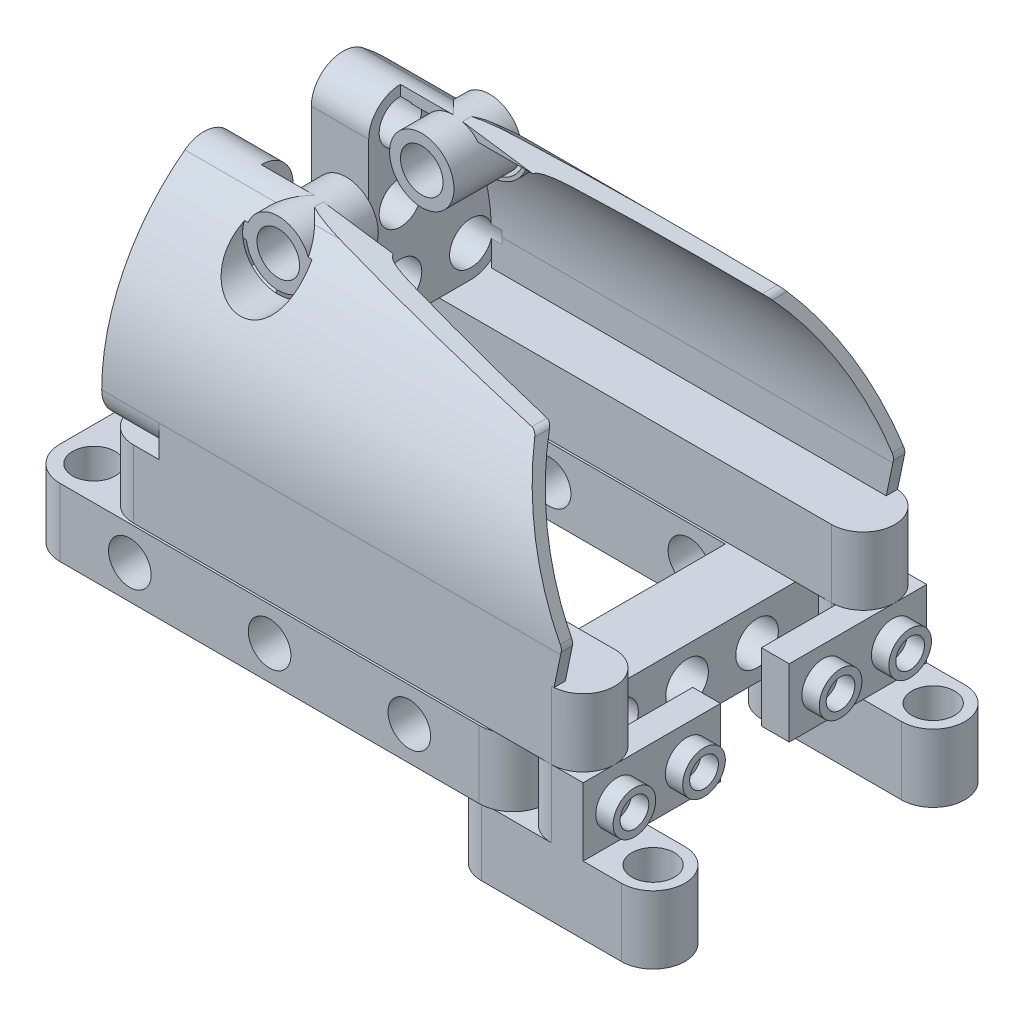
SolidWorks part; units mm, degrees
ref_plane "Front Plane" through (0, 0, 0) normal (0, 0, 1) x (1, 0, 0)
ref_plane "Top plane" through (0, 0, 0) normal (0, 1, 0) x (1, 0, 0)
ref_plane "Right plane" through (0, 0, 0) normal (1, 0, 0) x (0, 0, -1)
sketch "Sketch1" plane through (0, 0, 0) normal (0, 1, 0) x (1, 0, 0)
  line L0 (-8.05, 0) -> (8.05, 0) construction
  line L1 (-8.05, 3.65) -> (8.05, 3.65)
  line L2 (-8.05, -3.65) -> (8.05, -3.65)
  arc A0 (-8.05, 3.65) -> (-8.05, -3.65) centre (-8.05, 0) ccw
  arc A1 (8.05, -3.65) -> (8.05, 3.65) centre (8.05, 0) ccw
  point P2 (0, 0)
  point P7 (11.7, 0)
  point P9 (-11.7, 0)
  dimension "D1" = 7.3
  dimension "D2" = 23.4
extrude "Boss-Extrude1" add sketch "Sketch1" along normal blind 7.8
sketch "Sketch2" plane through (0, 7.8, 0) normal (0, 1, 0) x (1, 0, 0)
  line L0 (-52.6, 0) -> (-14.3812, 0) construction
  line L1 (-8.05, 3.9) -> (-56.25, 3.9)
  line L2 (-4.15, 0) -> (-4.15, -16.1)
  line L4 (-60.15, 0) -> (-60.15, -16.1)
  line L5 (-52.35, -16.1) -> (-52.35, -3.9)
  line L6 (-52.35, -3.9) -> (-11.95, -3.9)
  line L7 (-11.95, -3.9) -> (-11.95, -16.1)
  line L8 (-11.95, -16.1) -> (-4.15, -16.1)
  line L9 (-52.35, -16.1) -> (-60.15, -16.1)
  line L10 (-26.0708, -3.9) -> (-26.0708, 3.9) construction
  line L11 (-8.05, 0) -> (8.05, 0) construction
  line L12 (0, 3.65) -> (3.65, 3.65)
  line L13 (-8.05, 3.65) -> (8.05, 3.65) construction
  line L14 (3.65, 3.65) -> (3.65, -12.15)
  line L15 (3.65, -12.15) -> (0.45, -12.15)
  line L16 (0.45, -12.15) -> (0.45, -3.65)
  line L17 (-8.05, -3.65) -> (8.05, -3.65) construction
  line L18 (0, -3.65) -> (0.45, -3.65)
  arc A2 (-8.05, 3.9) -> (-4.15, 0) centre (-8.05, 0) cw
  arc A3 (-60.15, 0) -> (-56.25, 3.9) centre (-56.25, 0) cw
  arc A7 (-8.05, 3.65) -> (-8.05, -3.65) centre (-8.05, 0) ccw construction
  arc A8 (0, 3.65) -> (0, -3.65) centre (0, 0) ccw
  point P18 (-26.0708, 0)
  dimension "D1" = 56
  dimension "D2" = 7.8
  dimension "D3" = 20
  dimension "D4" = 15.8
  dimension "D5" = 3.2
extrude "Boss-Extrude2" add sketch "Sketch2" along normal blind 7.8 contours A2 L2 L8 L7 L6 L5 L9 L4 A3 L1 | A8 L18 L16 L15 L14 L12
sketch "Sketch3" plane through (0, 15.6, 0) normal (0, 1, 0) x (1, 0, 0)
  line L0 (-48.05, 0) -> (0, 0) construction
  line L1 (-48.05, 3.65) -> (0, 3.65)
  line L2 (-48.05, -3.65) -> (0, -3.65)
  arc A0 (-48.05, 3.65) -> (-48.05, -3.65) centre (-48.05, 0) ccw
  arc A1 (0, -3.65) -> (0, 3.65) centre (0, 0) ccw
  arc A2 (8.05, -3.65) -> (8.05, 3.65) centre (8.05, 0) ccw construction
  point P3 (-24.025, 0)
  point P11 (-51.7, 0)
  point P12 (3.65, 0)
  dimension "D1" = 55.35
extrude "Boss-Extrude3" add sketch "Sketch3" along normal blind 7.8
ref_plane "Plane1" through (-51.7, 0, 0) normal (-1, 0, 0) x (0, 0, 1)
sketch "Sketch5" plane through (-51.7, 0, 0) normal (-1, 0, 0) x (0, 0, 1)
  line L1 (3.65, 23.4) -> (-3.65, 23.4) construction
  line L2 (0, 23.4) -> (8.1, 23.4)
  line L3 (11.75, 27.05) -> (11.75, 43.25)
  arc A0 (-3.65, 27.05) -> (0, 23.4) centre (0, 27.05) ccw
  arc A1 (8.1, 23.4) -> (11.75, 27.05) centre (8.1, 27.05) ccw
  arc A2 (11.75, 43.25) -> (5.91, 46.17) centre (8.1, 43.25) ccw
  arc A3 (-3.65, 27.05) -> (5.91, 46.17) centre (20.25, 27.05) cw
  point P2 (-3.65, 27.05)
  point P4 (11.75, 27.05)
  point P8 (8.1, 46.9)
  point P9 (8.1, 23.4)
  dimension "D1" = 15.4
  dimension "D2" = 23.5
extrude "Boss-Extrude4" add sketch "Sketch5" against normal blind 6.6
sketch "Sketch6" plane through (-45.1, 0, 0) normal (1, 0, 0) x (0, 0, -1)
  line L0 (-8.1, 45.6) -> (-8.1, 46.9)
  line L2 (3.65, 27.05) -> (3.65, 23.4)
  line L3 (3.65, 23.4) -> (2.35, 23.4)
  line L4 (3.65, 23.4) -> (-3.65, 23.4) construction
  line L5 (2.35, 23.4) -> (2.35, 27.05)
  line L6 (2.35, 27.05) -> (3.65, 27.05) construction
  arc A1 (-5.91, 46.17) -> (-11.75, 43.25) centre (-8.1, 43.25) ccw construction
  arc A2 (3.65, 27.05) -> (-5.91, 46.17) centre (-20.25, 27.05) ccw construction
  arc A4 (-5.91, 46.17) -> (-8.1, 46.9) centre (-8.1, 43.25) ccw
  arc A5 (3.65, 27.05) -> (-5.91, 46.17) centre (-20.25, 27.05) ccw
  arc A7 (2.35, 27.05) -> (-6.69, 45.13) centre (-20.25, 27.05) ccw
  arc A8 (-6.69, 45.13) -> (-8.1, 45.6) centre (-8.1, 43.25) ccw
  arc A9 (-6.69, 45.13) -> (-10.45, 43.25) centre (-8.1, 43.25) ccw construction
  arc A10 (-5.91, 46.17) -> (-11.75, 43.25) centre (-8.1, 43.25) ccw construction
  arc A11 (0, 23.4) -> (3.65, 27.05) centre (0, 27.05) ccw construction
  arc A12 (0, 24.7) -> (2.35, 27.05) centre (0, 27.05) ccw construction
  dimension "D1" = 1.3
extrude "Boss-Extrude8" add sketch "Sketch6" along normal blind 46.3 separate body contours A5 A4 L0 A8 A7 L5 L3 L2
sketch "Sketch11" plane through (0, 0, -3.65) normal (0, 0, -1) x (-1, 0, 0)
  line L0 (39, 46.9) -> (7.8782, 42.4681)
  line L1 (51.7, 27.05) -> (51.7, 46.17) construction
  line L2 (7.1561, 41.9831) -> (-1.0054, 28.0326)
  line L3 (-1.2, 46.17) -> (-1.2, 27.05) construction
  line L4 (-1.1211, 27.3228) -> (-0.3, 23.4)
  line L5 (0, 23.4) -> (48.05, 23.4) construction
  line L6 (-0.3, 23.4) -> (-1.2, 23.4)
  line L7 (-1.2, 23.4) -> (-1.2, 27.7)
  line L8 (-1.2, 27.7) -> (-1.2, 46.9)
  line L9 (-1.2, 46.9) -> (39, 46.9)
  arc A0 (-1.0054, 28.0326) -> (-1.1211, 27.3228) centre (-0.1423, 27.5277) ccw
  arc A1 (7.8782, 42.4681) -> (7.1561, 41.9831) centre (8.0192, 41.4781) ccw
  point P20 (7.4, 42.4)
  dimension "D5" = 1
  dimension "D1" = 44.3
  dimension "D2" = 52
  dimension "D3" = 4.3
  dimension "D4" = 19
  dimension "D6" = 12.7
extrude "Cut-Extrude1" cut sketch "Sketch11" against normal through all
sketch "Sketch12" plane through (0, 0, 11.75) normal (0, 0, 1) x (1, 0, 0)
  circle A0 centre (-39, 43.2) radius 3.7
  dimension "D1" = 7.4
extrude "Boss-Extrude25" add sketch "Sketch12" against normal blind 7.8
sketch "Sketch13" plane through (0, 0, 3.95) normal (0, 0, -1) x (-1, 0, 0)
  line L0 (34.5273, 42.7047) -> (43.4727, 42.7047)
  arc A0 (34.5273, 42.7047) -> (43.4727, 42.7047) centre (39, 43.2) ccw
  dimension "D1" = 9
extrude "Boss-Extrude26" add sketch "Sketch13" along normal up to next
ref_plane "Plane3" through (0, 0, -1.05) normal (0, 0, 1) x (1, 0, 0)
sketch "Sketch14" plane through (0, 0, -1.05) normal (0, 0, 1) x (1, 0, 0)
  circle A0 centre (-39, 43.2) radius 4.1
  dimension "D1" = 8.2
extrude "Cut-Extrude2" cut sketch "Sketch14" along normal up to surface (5 mm away) up to face at (-39, 45.7146, 3.95)
sketch "Sketch15" plane through (3.65, 0, 0) normal (1, 0, 0) x (0, 0, -1)
  line L0 (-8.25, 11.7) -> (-0.25, 11.7) construction
  line L1 (-12.15, 15.6) -> (3.65, 15.6) construction
  line L2 (-4.25, 15.6) -> (-4.25, 7.8) construction
  line L3 (-3.65, 7.8) -> (-12.15, 7.8) construction
  circle A0 centre (-8.25, 11.7) radius 2.45
  circle A1 centre (-0.25, 11.7) radius 2.45
  circle A2 centre (-8.25, 11.7) radius 1.65
  circle A3 centre (-0.25, 11.7) radius 1.65
  point P8 (-4.25, 15.6)
  point P9 (-4.25, 11.7)
  point P14 (-10.7, 11.7)
  point P15 (-4.25, 11.7)
  point P16 (2.2, 11.7)
  dimension "D1" = 4.9
  dimension "D2" = 12.9
  dimension "D3" = 0.8
extrude "Boss-Extrude27" add sketch "Sketch15" along normal blind 2
sketch "Sketch16" plane through (-51.7, 0, 0) normal (-1, 0, 0) x (0, 0, 1)
  line L0 (8.1, 43.25) -> (8.1, 27.05) construction
  point P0 (8.1, 43.25)
  point P1 (8.1, 27.05)
  point P3 (0, 27.05)
  point P8 (8.1, 35.15)
sketch "Sketch17" plane through (0, 0, 11.75) normal (0, 0, 1) x (1, 0, 0)
  point P0 (-39, 43.2)
sketch "Sketch18" plane through (0, 7.8, 0) normal (0, -1, 0) x (1, 0, 0)
  line L0 (-8.05, 0) -> (-24.1167, 0) construction
  line L1 (-52.6, 0) -> (-14.3812, 0) construction
  line L2 (-24.1167, 0) -> (-40.1833, 0) construction
  line L3 (-40.1833, 0) -> (-56.25, 0) construction
  point P9 (-56.25, 0)
  point P10 (-40.1833, 0)
  point P11 (-24.1167, 0)
  point P12 (-8.05, 0)
sketch "Sketch19" plane through (0, 0, 0) normal (0, -1, 0) x (1, 0, 0)
  point P0 (8.05, 0)
sketch "Sketch20" plane through (0, 0, 3.9) normal (0, 0, 1) x (1, 0, 0)
  line L0 (-48.2167, 7.8) -> (-48.2167, 15.6) construction
  line L1 (-40.1833, 7.8) -> (-56.25, 7.8) construction
  line L2 (-52.35, 15.6) -> (-11.95, 15.6) construction
  line L3 (-32.15, 7.8) -> (-32.15, 15.6) construction
  line L4 (-24.1167, 7.8) -> (-40.1833, 7.8) construction
  line L5 (-8.05, 7.8) -> (-24.1167, 7.8) construction
  point P10 (-16.0833, 11.7)
  point P14 (-16.0833, 7.8)
  point P16 (-48.2167, 11.7)
  point P17 (-32.15, 11.7)
hole_wizard "HoleWzd1" positions "3DSketch1" profile "Sketch22" legacy
sketch3d "3DSketch1"
  line L0 (-8.05, 7.8, 3.9) -> (-24.1167, 7.8, 3.9) construction
  point P0 (-39, 43.2, 11.75)
  point P3 (-51.7, 43.25, 8.1)
  point P6 (-51.7, 35.15, 8.1)
  point P9 (-51.7, 27.05, 8.1)
  point P12 (-51.7, 27.05, 0)
  point P15 (8.05, 0, 0)
  point P18 (-16.0833, 7.8, 3.9)
  point P22 (-32.15, 11.7, 3.9)
  point P25 (-16.0833, 7.8, 3.9)
  point P27 (-48.2167, 11.7, 3.9)
  point P30 (-16.0833, 7.8, 3.9)
  point P32 (-56.25, 7.8, 0)
  point P35 (-24.1167, 7.8, 0)
  point P38 (-16.0833, 7.8, 3.9)
  point P40 (-16.0833, 7.8, 3.9)
  point P42 (-16.0833, 7.8, 3.9)
  point P44 (-16.0833, 7.8, 3.9)
  point P46 (-16.0833, 7.8, 3.9)
  point P48 (-16.0833, 7.8, 3.9)
  point P50 (-16.0833, 7.8, 3.9)
  point P52 (32.0633, 36.5039, 0)
  point P54 (-16.0833, 7.8, 3.9)
  point P55 (-16.0833, 7.8, 3.9)
  point P57 (-16.0833, 7.8, 3.9)
  point P59 (-16.0833, 7.8, 3.9)
  point P61 (-16.0833, 7.8, 3.9)
  point P64 (-16.0833, 11.7, 3.9)
sketch "Sketch22" plane through (-39, 43.2, 11.75) normal (1, 0, 0) x (0, -1, 0)
  line L0 (0, 0) -> (0, 7.85)
  line L1 (0, 7.85) -> (2.45, 7.85)
  line L2 (2.45, 7.85) -> (2.45, 0)
  line L3 (2.45, 0) -> (0, 0)
  line L4 (0, 110) -> (0, -10) construction
  dimension "Diameter" = 4.9
  dimension "Depth" = 7.85
ref_plane "Plane4" through (0, 0, 16.1) normal (0, 0, 1) x (1, 0, 0)
mirror "Mirror7" about plane through (0, 0, 16.1) normal (0, 0, 1) of bodies 113
sketch "Sketch24" plane through (-11.95, 0, 0) normal (-1, 0, 0) x (0, 0, 1)
  line L0 (8.05, 11.7) -> (24.15, 11.7) construction
  line L2 (3.9, 15.6) -> (28.3, 15.6) construction
  line L4 (16.1, 15.6) -> (16.1, 7.8) construction
  line L5 (3.9, 7.8) -> (28.3, 7.8) construction
  point P8 (16.1, 11.7)
  point P12 (24.15, 11.7)
  point P13 (16.1, 11.7)
  point P14 (8.05, 11.7)
  dimension "D1" = 16.1
sketch "Sketch25" plane through (-52.35, 0, 0) normal (1, 0, 0) x (0, 0, -1)
  line L0 (-8.05, 11.7) -> (-24.15, 11.7) construction
  line L1 (-8.05, 11.7) -> (-24.15, 11.7) construction
  point P2 (-16.1, 11.7)
  point P3 (-24.15, 11.7)
  point P5 (-8.05, 11.7)
hole_wizard "HoleWzd2" positions "3DSketch2" profile "Sketch26" legacy
sketch3d "3DSketch2"
  point P0 (-52.35, 11.7, 24.15)
  point P3 (-52.35, 11.7, 16.1)
  point P6 (-52.35, 11.7, 8.05)
  point P9 (-11.95, 11.7, 16.1)
  point P12 (-11.95, 11.7, 24.15)
  point P15 (-11.95, 11.7, 8.05)
sketch "Sketch26" plane through (-52.35, 11.7, 24.15) normal (0, 1, 0) x (0, 0, -1)
  line L0 (0, 0) -> (0, 7.85)
  line L1 (0, 7.85) -> (2.45, 7.85)
  line L2 (2.45, 7.85) -> (2.45, 0)
  line L3 (2.45, 0) -> (0, 0)
  line L4 (0, 110) -> (0, -10) construction
  dimension "Diameter" = 4.9
  dimension "Depth" = 7.85
